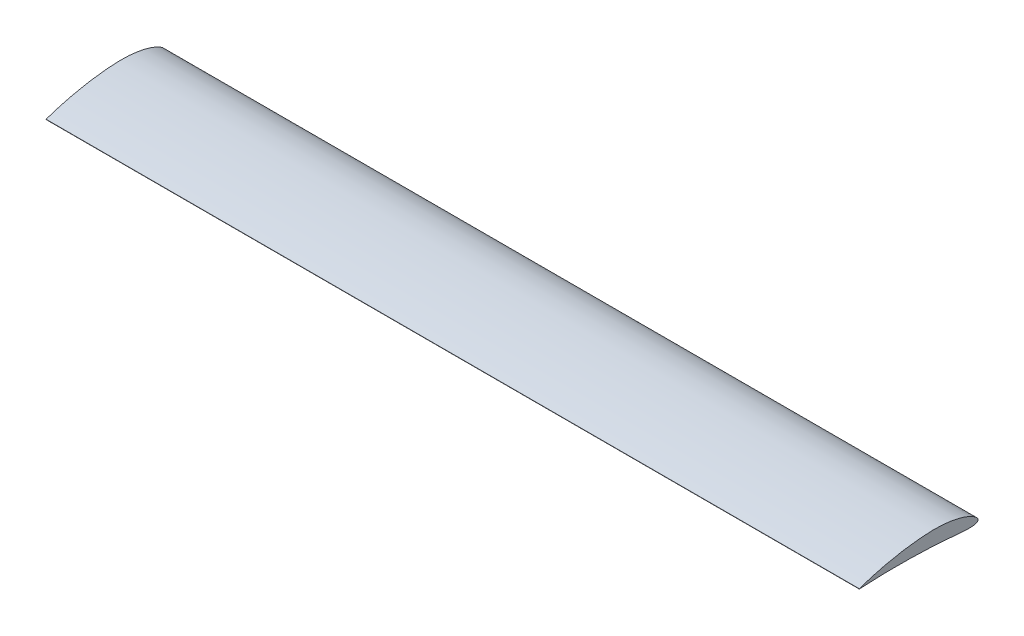
SolidWorks part; units mm, degrees
ref_plane "Front Plane" through (0, 0, 0) normal (0, 0, 1) x (1, 0, 0)
ref_plane "Top Plane" through (0, 0, 0) normal (0, 1, 0) x (1, 0, 0)
ref_plane "Right Plane" through (0, 0, 0) normal (1, 0, 0) x (0, 0, -1)
sketch3d "3DSketch3" plane through (0, 0, 0) normal (0, 0, 1) x (1, 0, 0)
  dimension "D1" = 2438.4
curve "Curve3"
  spline degree 3 poles (0, 0, 0) (0, -0.0634, 0.0198) (0, -0.1901, 0.0592) (0, -0.3772, 0.1273) (0, -0.5618, 0.2018) (0, -0.7437, 0.2832) (0, -0.923, 0.3715) (0, -1.0997, 0.4667) (0, -1.2737, 0.5687) (0, -1.4452, 0.6775) (0, -1.614, 0.7932) (0, -1.7802, 0.9157) (0, -1.9437, 1.045) (0, -2.1047, 1.181) (0, -2.2631, 1.3238) (0, -2.4188, 1.4735) (0, -2.5721, 1.6298) (0, -2.7222, 1.7933) (0, -2.8706, 1.9627) (0, -3.0158, 2.1392) (0, -3.1586, 2.3224) (0, -3.2988, 2.5123) (0, -3.4364, 2.7088) (0, -3.5714, 2.912) (0, -3.7039, 3.1219) (0, -3.8339, 3.3384) (0, -3.9613, 3.5614) (0, -4.0861, 3.7911) (0, -4.2084, 4.0274) (0, -4.3282, 4.2702) (0, -4.4454, 4.5196) (0, -4.5602, 4.7755) (0, -4.6724, 5.0379) (0, -4.7821, 5.3068) (0, -4.8894, 5.5822) (0, -4.9941, 5.8641) (0, -5.0964, 6.1524) (0, -5.1962, 6.4471) (0, -5.2935, 6.7483) (0, -5.3884, 7.0559) (0, -5.4809, 7.3698) (0, -5.5709, 7.6901) (0, -5.6585, 8.0167) (0, -5.7437, 8.3497) (0, -5.8264, 8.6889) (0, -5.9068, 9.0345) (0, -5.9848, 9.3863) (0, -6.0604, 9.7443) (0, -6.1337, 10.1086) (0, -6.2046, 10.4791) (0, -6.2732, 10.8558) (0, -6.3394, 11.2386) (0, -6.4033, 11.6276) (0, -6.4649, 12.0227) (0, -6.5242, 12.4239) (0, -6.5813, 12.8312) (0, -6.636, 13.2445) (0, -6.6885, 13.6639) (0, -6.7388, 14.0893) (0, -6.7868, 14.5207) (0, -6.8326, 14.958) (0, -6.8762, 15.4013) (0, -6.9176, 15.8506) (0, -6.9569, 16.3057) (0, -6.9939, 16.7667) (0, -7.0288, 17.2336) (0, -7.0616, 17.7063) (0, -7.0922, 18.1848) (0, -7.1208, 18.6691) (0, -7.1472, 19.1592) (0, -7.1716, 19.655) (0, -7.1939, 20.1565) (0, -7.2141, 20.6637) (0, -7.2323, 21.1766) (0, -7.2486, 21.6952) (0, -7.2628, 22.2193) (0, -7.275, 22.749) (0, -7.2852, 23.2844) (0, -7.2935, 23.8252) (0, -7.2999, 24.3716) (0, -7.3043, 24.9235) (0, -7.3069, 25.4808) (0, -7.3075, 26.0436) (0, -7.3063, 26.6118) (0, -7.3033, 27.1854) (0, -7.2984, 27.7644) (0, -7.2917, 28.3487) (0, -7.2832, 28.9383) (0, -7.273, 29.5332) (0, -7.2609, 30.1334) (0, -7.2472, 30.7389) (0, -7.2317, 31.3495) (0, -7.2145, 31.9653) (0, -7.1956, 32.5863) (0, -7.1751, 33.2124) (0, -7.1529, 33.8436) (0, -7.1291, 34.4799) (0, -7.1038, 35.1213) (0, -7.0768, 35.7677) (0, -7.0482, 36.4191) (0, -7.0182, 37.0755) (0, -6.9866, 37.7368) (0, -6.9534, 38.403) (0, -6.9189, 39.0741) (0, -6.8828, 39.7501) (0, -6.8453, 40.431) (0, -6.8064, 41.1166) (0, -6.7662, 41.807) (0, -6.7245, 42.5022) (0, -6.6815, 43.2022) (0, -6.6371, 43.9068) (0, -6.5915, 44.6161) (0, -6.5445, 45.3301) (0, -6.4963, 46.0486) (0, -6.4469, 46.7718) (0, -6.3962, 47.4996) (0, -6.3444, 48.2318) (0, -6.2914, 48.9686) (0, -6.2372, 49.7099) (0, -6.1819, 50.4557) (0, -6.1255, 51.2059) (0, -6.068, 51.9604) (0, -6.0095, 52.7194) (0, -5.9499, 53.4827) (0, -5.8894, 54.2503) (0, -5.8278, 55.0222) (0, -5.7653, 55.7984) (0, -5.7018, 56.5788) (0, -5.6375, 57.3635) (0, -5.5722, 58.1523) (0, -5.5061, 58.9453) (0, -5.4392, 59.7424) (0, -5.3714, 60.5436) (0, -5.3029, 61.3488) (0, -5.2336, 62.1581) (0, -5.1635, 62.9715) (0, -5.0927, 63.7888) (0, -5.0213, 64.6101) (0, -4.9492, 65.4353) (0, -4.8764, 66.2644) (0, -4.8031, 67.0974) (0, -4.7291, 67.9343) (0, -4.6546, 68.7749) (0, -4.5796, 69.6194) (0, -4.504, 70.4677) (0, -4.428, 71.3196) (0, -4.3515, 72.1753) (0, -4.2746, 73.0347) (0, -4.1972, 73.8977) (0, -4.1195, 74.7644) (0, -4.0414, 75.6346) (0, -3.9631, 76.5085) (0, -3.8844, 77.3858) (0, -3.8054, 78.2667) (0, -3.7262, 79.1511) (0, -3.6467, 80.0389) (0, -3.5671, 80.9302) (0, -3.4873, 81.8249) (0, -3.4073, 82.7229) (0, -3.3272, 83.6243) (0, -3.247, 84.529) (0, -3.1668, 85.437) (0, -3.0865, 86.3483) (0, -3.0062, 87.2628) (0, -2.926, 88.1805) (0, -2.8457, 89.1014) (0, -2.7656, 90.0255) (0, -2.6855, 90.9526) (0, -2.6055, 91.8829) (0, -2.5257, 92.8162) (0, -2.4461, 93.7526) (0, -2.3666, 94.692) (0, -2.2874, 95.6343) (0, -2.2084, 96.5796) (0, -2.1297, 97.5279) (0, -2.0514, 98.479) (0, -1.9733, 99.433) (0, -1.8956, 100.3898) (0, -1.8182, 101.3494) (0, -1.7413, 102.3118) (0, -1.6648, 103.277) (0, -1.5888, 104.2449) (0, -1.5132, 105.2155) (0, -1.4382, 106.1887) (0, -1.3636, 107.1646) (0, -1.2897, 108.1431) (0, -1.2163, 109.1241) (0, -1.1435, 110.1077) (0, -1.0714, 111.0938) (0, -0.9999, 112.0824) (0, -0.9291, 113.0735) (0, -0.8591, 114.067) (0, -0.7897, 115.0629) (0, -0.7211, 116.0611) (0, -0.6533, 117.0617) (0, -0.5863, 118.0646) (0, -0.5201, 119.0698) (0, -0.4548, 120.0772) (0, -0.3904, 121.0869) (0, -0.3268, 122.0987) (0, -0.2642, 123.1127) (0, -0.2025, 124.1288) (0, -0.1418, 125.147) (0, -0.0821, 126.1672) (0, -0.0234, 127.1895) (0, 0.0343, 128.2138) (0, 0.0908, 129.2401) (0, 0.1464, 130.2683) (0, 0.2008, 131.2984) (0, 0.2541, 132.3304) (0, 0.3062, 133.3643) (0, 0.3572, 134.3999) (0, 0.4069, 135.4374) (0, 0.4555, 136.4765) (0, 0.5028, 137.5174) (0, 0.5489, 138.56) (0, 0.5937, 139.6043) (0, 0.6372, 140.6501) (0, 0.6797, 141.7018) (0, 0.7205, 142.7639) (0, 0.7611, 143.8363) (0, 0.8019, 144.9147) (0, 0.8426, 145.9944) (0, 0.8833, 147.0755) (0, 0.9239, 148.1578) (0, 0.9644, 149.2414) (0, 1.0047, 150.3263) (0, 1.045, 151.4122) (0, 1.0852, 152.4994) (0, 1.1252, 153.5876) (0, 1.165, 154.6768) (0, 1.2047, 155.7671) (0, 1.2442, 156.8584) (0, 1.2835, 157.9505) (0, 1.3226, 159.0436) (0, 1.3615, 160.1375) (0, 1.4001, 161.2323) (0, 1.4385, 162.3278) (0, 1.4767, 163.424) (0, 1.5146, 164.5209) (0, 1.5522, 165.6185) (0, 1.5896, 166.7167) (0, 1.6266, 167.8154) (0, 1.6634, 168.9147) (0, 1.6998, 170.0145) (0, 1.7359, 171.1147) (0, 1.7717, 172.2153) (0, 1.8071, 173.3162) (0, 1.8422, 174.4175) (0, 1.8769, 175.5191) (0, 1.9113, 176.6209) (0, 1.9452, 177.7229) (0, 1.9788, 178.825) (0, 2.0119, 179.9273) (0, 2.0447, 181.0297) (0, 2.077, 182.132) (0, 2.1089, 183.2344) (0, 2.1404, 184.3367) (0, 2.1714, 185.4389) (0, 2.202, 186.541) (0, 2.2321, 187.6429) (0, 2.2617, 188.7446) (0, 2.2909, 189.846) (0, 2.3196, 190.9471) (0, 2.3478, 192.0478) (0, 2.3755, 193.1482) (0, 2.4027, 194.2482) (0, 2.4294, 195.3476) (0, 2.4556, 196.4466) (0, 2.4812, 197.545) (0, 2.5064, 198.6428) (0, 2.531, 199.7399) (0, 2.5551, 200.8364) (0, 2.5786, 201.9321) (0, 2.6016, 203.0271) (0, 2.624, 204.1213) (0, 2.6459, 205.2146) (0, 2.6672, 206.307) (0, 2.688, 207.3985) (0, 2.7082, 208.489) (0, 2.7278, 209.5785) (0, 2.7468, 210.6669) (0, 2.7653, 211.7542) (0, 2.7832, 212.8403) (0, 2.8005, 213.9253) (0, 2.8172, 215.009) (0, 2.8333, 216.0915) (0, 2.8488, 217.1726) (0, 2.8638, 218.2524) (0, 2.8781, 219.3307) (0, 2.8918, 220.4076) (0, 2.905, 221.483) (0, 2.9175, 222.5569) (0, 2.9294, 223.6292) (0, 2.9408, 224.6999) (0, 2.9515, 225.769) (0, 2.9616, 226.8363) (0, 2.9711, 227.9019) (0, 2.98, 228.9657) (0, 2.9883, 230.0277) (0, 2.996, 231.0878) (0, 3.0031, 232.146) (0, 3.0096, 233.2022) (0, 3.0155, 234.2564) (0, 3.0208, 235.3086) (0, 3.0255, 236.3587) (0, 3.0295, 237.4067) (0, 3.033, 238.4525) (0, 3.0359, 239.4962) (0, 3.0382, 240.5375) (0, 3.0399, 241.5766) (0, 3.0409, 242.6133) (0, 3.0414, 243.6477) (0, 3.0414, 244.6796) (0, 3.0407, 245.7091) (0, 3.0394, 246.7361) (0, 3.0376, 247.7605) (0, 3.0352, 248.7824) (0, 3.0322, 249.8016) (0, 3.0287, 250.8182) (0, 3.0245, 251.832) (0, 3.0199, 252.8431) (0, 3.0146, 253.8514) (0, 3.0088, 254.8569) (0, 3.0025, 255.8595) (0, 2.9956, 256.8592) (0, 2.9881, 257.856) (0, 2.9802, 258.8497) (0, 2.9716, 259.8404) (0, 2.9626, 260.828) (0, 2.953, 261.8126) (0, 2.943, 262.7939) (0, 2.9324, 263.7721) (0, 2.9213, 264.747) (0, 2.9097, 265.7186) (0, 2.8976, 266.6869) (0, 2.885, 267.6519) (0, 2.8719, 268.6135) (0, 2.8583, 269.5716) (0, 2.8443, 270.5262) (0, 2.8298, 271.4773) (0, 2.8148, 272.4249) (0, 2.7994, 273.3689) (0, 2.7835, 274.3092) (0, 2.7672, 275.2459) (0, 2.7505, 276.1788) (0, 2.7333, 277.108) (0, 2.7157, 278.0334) (0, 2.6977, 278.955) (0, 2.6793, 279.8726) (0, 2.6604, 280.7864) (0, 2.6412, 281.6963) (0, 2.6216, 282.6021) (0, 2.6016, 283.504) (0, 2.5813, 284.4017) (0, 2.5606, 285.2954) (0, 2.5395, 286.1849) (0, 2.518, 287.0703) (0, 2.4963, 287.9514) (0, 2.4742, 288.8283) (0, 2.4517, 289.701) (0, 2.429, 290.5693) (0, 2.4059, 291.4332) (0, 2.3825, 292.2927) (0, 2.3588, 293.1478) (0, 2.3349, 293.9985) (0, 2.3106, 294.8446) (0, 2.2861, 295.6862) (0, 2.2613, 296.5232) (0, 2.2363, 297.3556) (0, 2.211, 298.1834) (0, 2.1855, 299.0064) (0, 2.1597, 299.8248) (0, 2.1337, 300.6384) (0, 2.1075, 301.4472) (0, 2.0811, 302.2512) (0, 2.0545, 303.0503) (0, 2.0277, 303.8445) (0, 2.0008, 304.6338) (0, 1.9736, 305.4182) (0, 1.9463, 306.1975) (0, 1.9188, 306.9718) (0, 1.8912, 307.7411) (0, 1.8634, 308.5052) (0, 1.8355, 309.2643) (0, 1.8074, 310.0181) (0, 1.7793, 310.7668) (0, 1.751, 311.5103) (0, 1.7227, 312.2485) (0, 1.6942, 312.9814) (0, 1.6657, 313.709) (0, 1.6371, 314.4312) (0, 1.6084, 315.148) (0, 1.5796, 315.8594) (0, 1.5508, 316.5654) (0, 1.522, 317.2659) (0, 1.4931, 317.9609) (0, 1.4642, 318.6503) (0, 1.4353, 319.3342) (0, 1.4064, 320.0125) (0, 1.3774, 320.6851) (0, 1.3485, 321.3521) (0, 1.3195, 322.0133) (0, 1.2906, 322.6689) (0, 1.2618, 323.3187) (0, 1.2329, 323.9628) (0, 1.2041, 324.601) (0, 1.1754, 325.2334) (0, 1.1467, 325.86) (0, 1.118, 326.4806) (0, 1.0895, 327.0953) (0, 1.061, 327.7041) (0, 1.0326, 328.3069) (0, 1.0043, 328.9038) (0, 0.9761, 329.4946) (0, 0.9481, 330.0793) (0, 0.9201, 330.658) (0, 0.8923, 331.2305) (0, 0.8646, 331.797) (0, 0.837, 332.3572) (0, 0.8096, 332.9113) (0, 0.7823, 333.4592) (0, 0.7552, 334.0009) (0, 0.7282, 334.5363) (0, 0.7014, 335.0654) (0, 0.6748, 335.5883) (0, 0.6484, 336.1048) (0, 0.6222, 336.6149) (0, 0.5962, 337.1187) (0, 0.5704, 337.6161) (0, 0.5448, 338.1071) (0, 0.5194, 338.5916) (0, 0.4942, 339.0697) (0, 0.4693, 339.5413) (0, 0.4445, 340.0064) (0, 0.4201, 340.465) (0, 0.3959, 340.917) (0, 0.3719, 341.3625) (0, 0.3482, 341.8013) (0, 0.3247, 342.2336) (0, 0.3016, 342.6593) (0, 0.2787, 343.0782) (0, 0.2561, 343.4906) (0, 0.2337, 343.8962) (0, 0.2117, 344.2952) (0, 0.1899, 344.6874) (0, 0.1685, 345.0729) (0, 0.1473, 345.4516) (0, 0.1265, 345.8236) (0, 0.106, 346.1887) (0, 0.0858, 346.5471) (0, 0.0659, 346.8986) (0, 0.0464, 347.2433) (0, 0.027, 347.5812) (0, 0.0083, 347.9122) (0, -0.0102, 348.2362) (0, -0.0286, 348.5534) (0, -0.0462, 348.8637) (0, -0.0638, 349.167) (0, -0.0809, 349.4634) (0, -0.0977, 349.7529) (0, -0.1141, 350.0353) (0, -0.1301, 350.3108) (0, -0.1458, 350.5793) (0, -0.161, 350.8408) (0, -0.1759, 351.0952) (0, -0.1905, 351.3427) (0, -0.2046, 351.583) (0, -0.2183, 351.8164) (0, -0.2317, 352.0426) (0, -0.2447, 352.2618) (0, -0.2572, 352.4739) (0, -0.2694, 352.6789) (0, -0.2811, 352.8768) (0, -0.2925, 353.0675) (0, -0.3034, 353.2512) (0, -0.314, 353.4277) (0, -0.3241, 353.5971) (0, -0.3338, 353.7593) (0, -0.3431, 353.9144) (0, -0.352, 354.0623) (0, -0.3604, 354.203) (0, -0.3684, 354.3365) (0, -0.3761, 354.4629) (0, -0.3832, 354.5821) (0, -0.39, 354.6941) (0, -0.3963, 354.7989) (0, -0.4022, 354.8964) (0, -0.4077, 354.9868) (0, -0.4127, 355.07) (0, -0.4173, 355.1459) (0, -0.4214, 355.2146) (0, -0.4252, 355.2761) (0, -0.4285, 355.3304) (0, -0.4313, 355.3774) (0, -0.4337, 355.4172) (0, -0.4357, 355.4498) (0, -0.4372, 355.4751) (0, -0.4383, 355.4932) (0, -0.439, 355.5041) (0, -0.4393, 355.5089) (0, -0.4394, 355.5101) knots 0 0 0 0 0.000556 0.001111 0.001666 0.002222 0.00278 0.00334 0.003902 0.004469 0.00504 0.005616 0.006197 0.006785 0.00738 0.007983 0.008593 0.009214 0.009841 0.010479 0.011127 0.011786 0.012455 0.013136 0.013829 0.014533 0.01525 0.01598 0.016722 0.017478 0.018247 0.019029 0.019826 0.020637 0.021461 0.022301 0.023154 0.024023 0.024906 0.025805 0.026718 0.027647 0.028591 0.02955 0.030525 0.031515 0.032521 0.033542 0.034579 0.035632 0.036701 0.037785 0.038885 0.040001 0.041133 0.042281 0.043445 0.044625 0.04582 0.047032 0.048259 0.049503 0.050762 0.052037 0.053328 0.054635 0.055957 0.057296 0.05865 0.06002 0.061406 0.062807 0.064224 0.065656 0.067104 0.068568 0.070047 0.071541 0.073051 0.074576 0.076117 0.077673 0.079244 0.08083 0.082431 0.084047 0.085678 0.087324 0.088985 0.09066 0.092351 0.094056 0.095775 0.097509 0.099258 0.101021 0.102798 0.10459 0.106396 0.108216 0.11005 0.111898 0.11376 0.115636 0.117525 0.119428 0.121345 0.123276 0.12522 0.127177 0.129148 0.131132 0.133129 0.135139 0.137163 0.139199 0.141248 0.14331 0.145385 0.147472 0.149572 0.151684 0.153809 0.155946 0.158095 0.160257 0.16243 0.164616 0.166813 0.169023 0.171244 0.173476 0.175721 0.177977 0.180244 0.182523 0.184813 0.187114 0.189426 0.191749 0.194083 0.196428 0.198784 0.20115 0.203527 0.205915 0.208313 0.210721 0.21314 0.215569 0.218008 0.220456 0.222915 0.225384 0.227862 0.23035 0.232848 0.235355 0.237872 0.240398 0.242933 0.245478 0.248031 0.250593 0.253165 0.255745 0.258334 0.260932 0.263538 0.266153 0.268776 0.271407 0.274047 0.276695 0.27935 0.282014 0.284686 0.287366 0.290053 0.292748 0.29545 0.29816 0.300878 0.303602 0.306334 0.309073 0.311819 0.314572 0.317332 0.320099 0.322872 0.325652 0.328439 0.331232 0.334031 0.336836 0.339648 0.342466 0.34529 0.34812 0.350956 0.353797 0.356644 0.359497 0.362355 0.365219 0.368088 0.370962 0.373841 0.376726 0.379615 0.382509 0.385408 0.388312 0.391221 0.394134 0.397051 0.399973 0.402899 0.405865 0.408873 0.411885 0.414901 0.417921 0.420944 0.423971 0.427001 0.430035 0.433071 0.436111 0.439153 0.442199 0.445246 0.448297 0.45135 0.454405 0.457463 0.460523 0.463585 0.466648 0.469714 0.472781 0.475849 0.47892 0.481991 0.485064 0.488137 0.491212 0.494288 0.497364 0.500441 0.503518 0.506596 0.509674 0.512753 0.515831 0.518909 0.521987 0.525065 0.528142 0.531219 0.534296 0.537371 0.540445 0.543519 0.546591 0.549663 0.552733 0.555801 0.558868 0.561933 0.564996 0.568057 0.571117 0.574174 0.577228 0.580281 0.583331 0.586378 0.589422 0.592464 0.595502 0.598538 0.60157 0.604599 0.607624 0.610646 0.613664 0.616678 0.619688 0.622694 0.625696 0.628694 0.631687 0.634676 0.63766 0.64064 0.643614 0.646584 0.649548 0.652507 0.655461 0.658409 0.661352 0.664289 0.66722 0.670145 0.673065 0.675978 0.678884 0.681785 0.684679 0.687566 0.690446 0.69332 0.696186 0.699046 0.701898 0.704743 0.707581 0.710411 0.713233 0.716048 0.718854 0.721653 0.724443 0.727226 0.729999 0.732765 0.735522 0.73827 0.741009 0.74374 0.746461 0.749174 0.751877 0.75457 0.757255 0.759929 0.762594 0.765249 0.767895 0.77053 0.773155 0.77577 0.778374 0.780968 0.783552 0.786125 0.788687 0.791238 0.793778 0.796307 0.798825 0.801332 0.803827 0.806311 0.808783 0.811243 0.813691 0.816128 0.818552 0.820965 0.823365 0.825753 0.828128 0.830491 0.832841 0.835178 0.837503 0.839814 0.842113 0.844398 0.84667 0.848929 0.851174 0.853406 0.855624 0.857829 0.86002 0.862196 0.864359 0.866508 0.868642 0.870762 0.872868 0.874959 0.877036 0.879098 0.881145 0.883178 0.885195 0.887198 0.889185 0.891157 0.893114 0.895056 0.896982 0.898892 0.900787 0.902667 0.90453 0.906378 0.908209 0.910025 0.911824 0.913608 0.915375 0.917125 0.91886 0.920577 0.922279 0.923963 0.925631 0.927282 0.928916 0.930533 0.932133 0.933716 0.935282 0.93683 0.938362 0.939875 0.941372 0.942851 0.944312 0.945756 0.947181 0.94859 0.94998 0.951352 0.952707 0.954043 0.955361 0.956661 0.957943 0.959206 0.960452 0.961678 0.962887 0.964077 0.965248 0.966401 0.967535 0.96865 0.969746 0.970824 0.971883 0.972923 0.973944 0.974945 0.975928 0.976892 0.977837 0.978762 0.979668 0.980555 0.981422 0.98227 0.983099 0.983908 0.984698 0.985468 0.986219 0.98695 0.987662 0.988353 0.989026 0.989678 0.990311 0.990923 0.991517 0.99209 0.992643 0.993177 0.99369 0.994184 0.994657 0.995111 0.995544 0.995958 0.996352 0.996725 0.997078 0.997412 0.997725 0.998018 0.998291 0.998543 0.998776 0.998988 0.99918 0.999352 0.999504 0.999636 0.999747 0.999838 0.999909 0.99996 0.99999 1 1 1 1
curve "Curve4"
  spline degree 3 poles (0, 0, 0) (0, 0.0638, -0.0184) (0, 0.1913, -0.0552) (0, 0.385, -0.1013) (0, 0.5801, -0.1407) (0, 0.7768, -0.1727) (0, 0.9752, -0.1976) (0, 1.1751, -0.2151) (0, 1.3767, -0.2255) (0, 1.5798, -0.2285) (0, 1.7845, -0.2243) (0, 1.9908, -0.2128) (0, 2.1987, -0.1941) (0, 2.4081, -0.168) (0, 2.6191, -0.1347) (0, 2.8317, -0.0941) (0, 3.0458, -0.0461) (0, 3.2614, 0.0091) (0, 3.4786, 0.0716) (0, 3.6973, 0.1414) (0, 3.9175, 0.2185) (0, 4.1392, 0.303) (0, 4.3625, 0.3947) (0, 4.5872, 0.4938) (0, 4.8133, 0.6002) (0, 5.041, 0.7139) (0, 5.2701, 0.8349) (0, 5.5006, 0.9632) (0, 5.7325, 1.0989) (0, 5.9659, 1.2419) (0, 6.2006, 1.3922) (0, 6.4368, 1.5498) (0, 6.6743, 1.7147) (0, 6.9131, 1.887) (0, 7.1533, 2.0666) (0, 7.3948, 2.2535) (0, 7.6375, 2.4477) (0, 7.8816, 2.6493) (0, 8.1269, 2.8582) (0, 8.3735, 3.0743) (0, 8.6213, 3.2978) (0, 8.8703, 3.5286) (0, 9.1204, 3.7667) (0, 9.3718, 4.0122) (0, 9.6242, 4.2649) (0, 9.8778, 4.5249) (0, 10.1325, 4.7921) (0, 10.3882, 5.0667) (0, 10.645, 5.3486) (0, 10.9028, 5.6377) (0, 11.1616, 5.9341) (0, 11.4214, 6.2378) (0, 11.6822, 6.5487) (0, 11.9438, 6.8668) (0, 12.2064, 7.1922) (0, 12.4698, 7.5249) (0, 12.734, 7.8648) (0, 12.9991, 8.2118) (0, 13.265, 8.5661) (0, 13.5316, 8.9276) (0, 13.7989, 9.2963) (0, 14.067, 9.6722) (0, 14.3357, 10.0553) (0, 14.6051, 10.4455) (0, 14.875, 10.8428) (0, 15.1456, 11.2473) (0, 15.4167, 11.659) (0, 15.6883, 12.0777) (0, 15.9604, 12.5036) (0, 16.233, 12.9366) (0, 16.5059, 13.3766) (0, 16.7793, 13.8237) (0, 17.0531, 14.2779) (0, 17.3271, 14.7391) (0, 17.6015, 15.2073) (0, 17.8761, 15.6825) (0, 18.1509, 16.1648) (0, 18.4259, 16.654) (0, 18.7011, 17.1502) (0, 18.9764, 17.6533) (0, 19.2518, 18.1634) (0, 19.5272, 18.6804) (0, 19.8026, 19.2042) (0, 20.078, 19.735) (0, 20.3534, 20.2726) (0, 20.6287, 20.8171) (0, 20.9038, 21.3684) (0, 21.1787, 21.9265) (0, 21.4535, 22.4914) (0, 21.728, 23.0631) (0, 22.0023, 23.6415) (0, 22.2762, 24.2266) (0, 22.5498, 24.8185) (0, 22.8229, 25.417) (0, 23.0957, 26.0222) (0, 23.368, 26.634) (0, 23.6398, 27.2524) (0, 23.911, 27.8775) (0, 24.1817, 28.5091) (0, 24.4517, 29.1472) (0, 24.7211, 29.7919) (0, 24.9898, 30.443) (0, 25.2577, 31.1007) (0, 25.5249, 31.7648) (0, 25.7913, 32.4353) (0, 26.0568, 33.1122) (0, 26.3214, 33.7954) (0, 26.5851, 34.485) (0, 26.8478, 35.1809) (0, 27.1096, 35.8831) (0, 27.3702, 36.5916) (0, 27.6298, 37.3062) (0, 27.8883, 38.0271) (0, 28.1456, 38.7542) (0, 28.4017, 39.4873) (0, 28.6566, 40.2266) (0, 28.9102, 40.972) (0, 29.1625, 41.7234) (0, 29.4134, 42.4808) (0, 29.6629, 43.2442) (0, 29.911, 44.0136) (0, 30.1577, 44.7888) (0, 30.4028, 45.57) (0, 30.6464, 46.357) (0, 30.8884, 47.1498) (0, 31.1287, 47.9484) (0, 31.3674, 48.7528) (0, 31.6044, 49.5628) (0, 31.8397, 50.3786) (0, 32.0732, 51.2) (0, 32.3049, 52.0269) (0, 32.5347, 52.8595) (0, 32.7627, 53.6976) (0, 32.9887, 54.5412) (0, 33.2128, 55.3902) (0, 33.4349, 56.2446) (0, 33.6549, 57.1045) (0, 33.8729, 57.9697) (0, 34.0888, 58.8401) (0, 34.3026, 59.7159) (0, 34.5141, 60.5968) (0, 34.7235, 61.483) (0, 34.9306, 62.3743) (0, 35.1355, 63.2707) (0, 35.338, 64.1721) (0, 35.5382, 65.0786) (0, 35.736, 65.99) (0, 35.9314, 66.9064) (0, 36.1244, 67.8277) (0, 36.3149, 68.7538) (0, 36.5029, 69.6847) (0, 36.6883, 70.6204) (0, 36.8712, 71.5608) (0, 37.0514, 72.5059) (0, 37.229, 73.4556) (0, 37.404, 74.4099) (0, 37.5762, 75.3688) (0, 37.7458, 76.3321) (0, 37.9125, 77.2999) (0, 38.0765, 78.2721) (0, 38.2377, 79.2486) (0, 38.396, 80.2295) (0, 38.5514, 81.2146) (0, 38.704, 82.204) (0, 38.8536, 83.1975) (0, 39.0002, 84.1951) (0, 39.1439, 85.1968) (0, 39.2846, 86.2026) (0, 39.4222, 87.2123) (0, 39.5567, 88.2259) (0, 39.6882, 89.2434) (0, 39.8166, 90.2648) (0, 39.9418, 91.2899) (0, 40.0639, 92.3188) (0, 40.1828, 93.3514) (0, 40.2985, 94.3876) (0, 40.4109, 95.4274) (0, 40.5202, 96.4707) (0, 40.6261, 97.5175) (0, 40.7287, 98.5677) (0, 40.8281, 99.6213) (0, 40.9241, 100.6783) (0, 41.0167, 101.7385) (0, 41.106, 102.8019) (0, 41.1919, 103.8686) (0, 41.2744, 104.9383) (0, 41.3534, 106.0112) (0, 41.429, 107.087) (0, 41.5011, 108.1658) (0, 41.5698, 109.2476) (0, 41.635, 110.3322) (0, 41.6966, 111.4196) (0, 41.7548, 112.5098) (0, 41.8094, 113.6026) (0, 41.8604, 114.6982) (0, 41.9079, 115.7963) (0, 41.9518, 116.897) (0, 41.9921, 118.0002) (0, 42.0288, 119.1058) (0, 42.0619, 120.2138) (0, 42.0913, 121.3241) (0, 42.1173, 122.4368) (0, 42.139, 123.5516) (0, 42.1592, 124.6686) (0, 42.1676, 125.7878) (0, 42.1543, 126.9092) (0, 42.1994, 128.032) (0, 42.1931, 129.1574) (0, 42.196, 130.2845) (0, 42.1917, 131.4134) (0, 42.1846, 132.5441) (0, 42.1736, 133.6766) (0, 42.1589, 134.8108) (0, 42.1405, 135.9466) (0, 42.1183, 137.0839) (0, 42.0925, 138.2228) (0, 42.0629, 139.3632) (0, 42.0295, 140.505) (0, 41.9927, 141.6439) (0, 41.9519, 142.7753) (0, 41.9085, 143.8991) (0, 41.8633, 145.0197) (0, 41.8158, 146.1414) (0, 41.7661, 147.2644) (0, 41.7142, 148.3885) (0, 41.66, 149.5137) (0, 41.6037, 150.64) (0, 41.5452, 151.7672) (0, 41.4845, 152.8954) (0, 41.4216, 154.0245) (0, 41.3565, 155.1544) (0, 41.2893, 156.2851) (0, 41.2199, 157.4166) (0, 41.1484, 158.5488) (0, 41.0747, 159.6817) (0, 40.9989, 160.8151) (0, 40.921, 161.9492) (0, 40.841, 163.0837) (0, 40.7588, 164.2187) (0, 40.6746, 165.3541) (0, 40.5883, 166.4899) (0, 40.4999, 167.626) (0, 40.4094, 168.7624) (0, 40.3169, 169.8991) (0, 40.2223, 171.0359) (0, 40.1257, 172.1728) (0, 40.0271, 173.3098) (0, 39.9265, 174.4469) (0, 39.8238, 175.5839) (0, 39.7192, 176.7209) (0, 39.6126, 177.8578) (0, 39.504, 178.9945) (0, 39.3935, 180.1311) (0, 39.281, 181.2674) (0, 39.1666, 182.4033) (0, 39.0503, 183.539) (0, 38.9321, 184.6743) (0, 38.8119, 185.8091) (0, 38.6899, 186.9434) (0, 38.5661, 188.0773) (0, 38.4404, 189.2105) (0, 38.3128, 190.3431) (0, 38.1834, 191.4751) (0, 38.0523, 192.6063) (0, 37.9193, 193.7368) (0, 37.7845, 194.8665) (0, 37.648, 195.9953) (0, 37.5097, 197.1232) (0, 37.3697, 198.2502) (0, 37.228, 199.3761) (0, 37.0845, 200.5011) (0, 36.9394, 201.6249) (0, 36.7926, 202.7477) (0, 36.6441, 203.8692) (0, 36.494, 204.9895) (0, 36.3423, 206.1086) (0, 36.1889, 207.2263) (0, 36.034, 208.3427) (0, 35.8775, 209.4577) (0, 35.7194, 210.5712) (0, 35.5598, 211.6833) (0, 35.3986, 212.7938) (0, 35.236, 213.9027) (0, 35.0718, 215.01) (0, 34.9062, 216.1157) (0, 34.7391, 217.2196) (0, 34.5706, 218.3217) (0, 34.4007, 219.4221) (0, 34.2293, 220.5206) (0, 34.0566, 221.6172) (0, 33.8825, 222.7119) (0, 33.707, 223.8046) (0, 33.5303, 224.8953) (0, 33.3522, 225.9839) (0, 33.1728, 227.0704) (0, 32.9921, 228.1547) (0, 32.8102, 229.2369) (0, 32.6271, 230.3168) (0, 32.4427, 231.3944) (0, 32.2571, 232.4697) (0, 32.0704, 233.5427) (0, 31.8825, 234.6132) (0, 31.6935, 235.6813) (0, 31.5033, 236.7469) (0, 31.3121, 237.81) (0, 31.1197, 238.8704) (0, 30.9263, 239.9283) (0, 30.7319, 240.9835) (0, 30.5365, 242.036) (0, 30.34, 243.0858) (0, 30.1426, 244.1328) (0, 29.9443, 245.1769) (0, 29.7449, 246.2182) (0, 29.5447, 247.2566) (0, 29.3436, 248.2921) (0, 29.1416, 249.3245) (0, 28.9388, 250.354) (0, 28.7351, 251.3804) (0, 28.5307, 252.4036) (0, 28.3254, 253.4238) (0, 28.1194, 254.4407) (0, 27.9126, 255.4544) (0, 27.7051, 256.4649) (0, 27.4969, 257.472) (0, 27.2881, 258.4759) (0, 27.0785, 259.4763) (0, 26.8684, 260.4733) (0, 26.6576, 261.4669) (0, 26.4463, 262.457) (0, 26.2343, 263.4435) (0, 26.0219, 264.4265) (0, 25.8089, 265.4059) (0, 25.5954, 266.3816) (0, 25.3814, 267.3537) (0, 25.167, 268.322) (0, 24.9521, 269.2866) (0, 24.7368, 270.2474) (0, 24.5212, 271.2043) (0, 24.3051, 272.1574) (0, 24.0888, 273.1066) (0, 23.8721, 274.0519) (0, 23.6551, 274.9932) (0, 23.4378, 275.9305) (0, 23.2203, 276.8637) (0, 23.0026, 277.7929) (0, 22.7847, 278.718) (0, 22.5665, 279.6389) (0, 22.3483, 280.5556) (0, 22.1299, 281.4682) (0, 21.9113, 282.3764) (0, 21.6927, 283.2804) (0, 21.4741, 284.1801) (0, 21.2553, 285.0754) (0, 21.0366, 285.9664) (0, 20.8179, 286.8529) (0, 20.5992, 287.735) (0, 20.3805, 288.6126) (0, 20.162, 289.4856) (0, 19.9435, 290.3542) (0, 19.7252, 291.2181) (0, 19.507, 292.0775) (0, 19.2889, 292.9322) (0, 19.0711, 293.7822) (0, 18.8535, 294.6275) (0, 18.6361, 295.4681) (0, 18.419, 296.3039) (0, 18.2022, 297.1349) (0, 17.9857, 297.9611) (0, 17.7695, 298.7825) (0, 17.5537, 299.5989) (0, 17.3383, 300.4104) (0, 17.1233, 301.217) (0, 16.9087, 302.0186) (0, 16.6945, 302.8152) (0, 16.4809, 303.6068) (0, 16.2677, 304.3933) (0, 16.0551, 305.1747) (0, 15.843, 305.951) (0, 15.6315, 306.7221) (0, 15.4205, 307.4881) (0, 15.2102, 308.2488) (0, 15.0006, 309.0043) (0, 14.7916, 309.7546) (0, 14.5833, 310.4996) (0, 14.3757, 311.2392) (0, 14.1688, 311.9736) (0, 13.9627, 312.7025) (0, 13.7573, 313.4261) (0, 13.5528, 314.1443) (0, 13.3491, 314.857) (0, 13.1463, 315.5642) (0, 12.9443, 316.266) (0, 12.7432, 316.9622) (0, 12.543, 317.6529) (0, 12.3438, 318.338) (0, 12.1455, 319.0176) (0, 11.9482, 319.6915) (0, 11.752, 320.3598) (0, 11.5567, 321.0224) (0, 11.3625, 321.6793) (0, 11.1694, 322.3306) (0, 10.9774, 322.9761) (0, 10.7865, 323.6158) (0, 10.5967, 324.2498) (0, 10.4081, 324.8779) (0, 10.2207, 325.5003) (0, 10.0345, 326.1168) (0, 9.8495, 326.7274) (0, 9.6658, 327.3322) (0, 9.4833, 327.931) (0, 9.3021, 328.5239) (0, 9.1223, 329.1109) (0, 8.9437, 329.6919) (0, 8.7665, 330.2669) (0, 8.5907, 330.8359) (0, 8.4163, 331.3989) (0, 8.2433, 331.9558) (0, 8.0718, 332.5067) (0, 7.9016, 333.0515) (0, 7.733, 333.5902) (0, 7.5659, 334.1227) (0, 7.4002, 334.6492) (0, 7.2362, 335.1694) (0, 7.0736, 335.6835) (0, 6.9126, 336.1914) (0, 6.7533, 336.6931) (0, 6.5955, 337.1885) (0, 6.4394, 337.6777) (0, 6.2849, 338.1607) (0, 6.1321, 338.6374) (0, 5.9809, 339.1078) (0, 5.8315, 339.5718) (0, 5.6838, 340.0296) (0, 5.5378, 340.481) (0, 5.3936, 340.926) (0, 5.2511, 341.3647) (0, 5.1105, 341.797) (0, 4.9716, 342.2229) (0, 4.8346, 342.6424) (0, 4.6994, 343.0554) (0, 4.5661, 343.462) (0, 4.4346, 343.8622) (0, 4.305, 344.2559) (0, 4.1774, 344.6431) (0, 4.0516, 345.0238) (0, 3.9278, 345.398) (0, 3.8059, 345.7657) (0, 3.686, 346.1268) (0, 3.5681, 346.4814) (0, 3.4521, 346.8294) (0, 3.3385, 347.171) (0, 3.2253, 347.5055) (0, 3.12, 347.8366) (0, 2.9939, 348.1528) (0, 2.8977, 348.4717) (0, 2.7952, 348.7798) (0, 2.6918, 349.0804) (0, 2.5994, 349.3774) (0, 2.5004, 349.6649) (0, 2.4056, 349.947) (0, 2.3123, 350.2222) (0, 2.2214, 350.4907) (0, 2.1326, 350.7526) (0, 2.0459, 351.0078) (0, 1.9614, 351.2562) (0, 1.8792, 351.498) (0, 1.7991, 351.733) (0, 1.7212, 351.9613) (0, 1.6456, 352.1828) (0, 1.5722, 352.3977) (0, 1.501, 352.6057) (0, 1.432, 352.807) (0, 1.3654, 353.0016) (0, 1.3009, 353.1894) (0, 1.2388, 353.3704) (0, 1.1789, 353.5446) (0, 1.1214, 353.712) (0, 1.0661, 353.8727) (0, 1.0131, 354.0265) (0, 0.9624, 354.1736) (0, 0.9141, 354.3138) (0, 0.8681, 354.4472) (0, 0.8243, 354.5738) (0, 0.783, 354.6936) (0, 0.7439, 354.8066) (0, 0.7072, 354.9127) (0, 0.6729, 355.012) (0, 0.6409, 355.1045) (0, 0.6112, 355.1901) (0, 0.5839, 355.2689) (0, 0.559, 355.3408) (0, 0.5364, 355.4059) (0, 0.5162, 355.4642) (0, 0.4984, 355.5156) (0, 0.483, 355.5602) (0, 0.4699, 355.5979) (0, 0.4592, 355.6287) (0, 0.4509, 355.6527) (0, 0.4449, 355.6698) (0, 0.4413, 355.6801) (0, 0.4397, 355.6847) (0, 0.4394, 355.6858) knots 0 0 0 0 0.000533 0.001065 0.001598 0.002131 0.002665 0.003202 0.003742 0.004285 0.004833 0.005386 0.005944 0.006508 0.00708 0.007659 0.008245 0.008841 0.009445 0.01006 0.010684 0.011319 0.011964 0.012621 0.01329 0.013971 0.014664 0.01537 0.016089 0.016821 0.017567 0.018327 0.0191 0.019888 0.020691 0.021508 0.02234 0.023187 0.024049 0.024927 0.02582 0.026728 0.027653 0.028593 0.029548 0.03052 0.031508 0.032513 0.033533 0.03457 0.035623 0.036692 0.037778 0.03888 0.039999 0.041135 0.042287 0.043456 0.044641 0.045843 0.047062 0.048297 0.04955 0.050819 0.052104 0.053407 0.054726 0.056061 0.057414 0.058783 0.060169 0.061571 0.062991 0.064426 0.065879 0.067348 0.068833 0.070335 0.071853 0.073388 0.07494 0.076507 0.078091 0.079692 0.081308 0.082941 0.08459 0.086255 0.087936 0.089633 0.091346 0.093075 0.09482 0.096581 0.098358 0.10015 0.101958 0.103781 0.10562 0.107475 0.109344 0.11123 0.11313 0.115046 0.116977 0.118923 0.120884 0.122859 0.12485 0.126856 0.128876 0.130911 0.13296 0.135024 0.137103 0.139196 0.141303 0.143424 0.145559 0.147709 0.149872 0.152049 0.15424 0.156445 0.158664 0.160896 0.163141 0.1654 0.167672 0.169957 0.172256 0.174567 0.176892 0.179229 0.181579 0.183942 0.186317 0.188705 0.191105 0.193517 0.195942 0.198379 0.200828 0.203289 0.205761 0.208246 0.210742 0.213249 0.215768 0.218299 0.220841 0.223393 0.225957 0.228532 0.231118 0.233714 0.236322 0.238939 0.241568 0.244206 0.246855 0.249514 0.252183 0.254862 0.257551 0.26025 0.262958 0.265676 0.268403 0.271139 0.273885 0.27664 0.279404 0.282177 0.284959 0.287749 0.290548 0.293355 0.296171 0.298995 0.301827 0.304668 0.307516 0.310372 0.313236 0.316107 0.318986 0.321873 0.324766 0.327667 0.330575 0.33349 0.336412 0.33934 0.342275 0.345217 0.348165 0.351119 0.35408 0.357046 0.360019 0.362997 0.365982 0.368971 0.371967 0.374967 0.377974 0.380985 0.384002 0.387023 0.390049 0.39308 0.396116 0.399156 0.4022 0.405249 0.408302 0.411359 0.41442 0.417451 0.420448 0.42345 0.426455 0.429463 0.432474 0.435489 0.438507 0.441528 0.444552 0.447578 0.450607 0.453639 0.456672 0.459708 0.462747 0.465787 0.468829 0.471873 0.474918 0.477965 0.481014 0.484064 0.487114 0.490166 0.493219 0.496273 0.499327 0.502382 0.505438 0.508493 0.511549 0.514605 0.517661 0.520717 0.523773 0.526828 0.529883 0.532937 0.53599 0.539043 0.542094 0.545144 0.548194 0.551241 0.554288 0.557332 0.560375 0.563417 0.566456 0.569493 0.572528 0.575561 0.578591 0.581619 0.584644 0.587666 0.590685 0.593702 0.596715 0.599725 0.602732 0.605735 0.608734 0.61173 0.614722 0.61771 0.620694 0.623674 0.626649 0.62962 0.632587 0.635548 0.638506 0.641458 0.644405 0.647347 0.650284 0.653215 0.656141 0.659061 0.661976 0.664885 0.667788 0.670684 0.673575 0.67646 0.679338 0.682209 0.685074 0.687932 0.690784 0.693628 0.696465 0.699296 0.702119 0.704934 0.707742 0.710543 0.713335 0.71612 0.718897 0.721666 0.724426 0.727179 0.729923 0.732658 0.735385 0.738104 0.740813 0.743513 0.746205 0.748887 0.75156 0.754224 0.756878 0.759523 0.762158 0.764783 0.767399 0.770004 0.7726 0.775185 0.77776 0.780324 0.782879 0.785422 0.787955 0.790477 0.792988 0.795488 0.797977 0.800455 0.802922 0.805377 0.807821 0.810253 0.812673 0.815082 0.817479 0.819863 0.822236 0.824597 0.826945 0.829281 0.831605 0.833916 0.836215 0.8385 0.840773 0.843033 0.84528 0.847514 0.849735 0.851943 0.854137 0.856318 0.858485 0.860639 0.862779 0.864905 0.867017 0.869116 0.8712 0.87327 0.875326 0.877368 0.879396 0.881409 0.883407 0.885391 0.88736 0.889314 0.891254 0.893178 0.895088 0.896982 0.898861 0.900725 0.902574 0.904407 0.906225 0.908028 0.909814 0.911585 0.913341 0.91508 0.916804 0.918511 0.920203 0.921878 0.923537 0.92518 0.926807 0.928417 0.930011 0.931588 0.933149 0.934693 0.936221 0.937731 0.939225 0.940702 0.942162 0.943605 0.945031 0.94644 0.947831 0.949206 0.950563 0.951902 0.953225 0.954529 0.955817 0.957086 0.958338 0.959573 0.960789 0.961988 0.963169 0.964332 0.965477 0.966605 0.967714 0.968805 0.969878 0.970933 0.97197 0.972988 0.973988 0.97497 0.975933 0.976878 0.977805 0.978722 0.979608 0.980478 0.98133 0.98216 0.982975 0.983771 0.984549 0.985308 0.986048 0.986769 0.987471 0.988155 0.988819 0.989465 0.990091 0.990699 0.991287 0.991857 0.992407 0.992939 0.993451 0.993944 0.994418 0.994872 0.995308 0.995724 0.996121 0.996499 0.996857 0.997196 0.997516 0.997817 0.998098 0.99836 0.998602 0.998825 0.999029 0.999214 0.999379 0.999524 0.99965 0.999757 0.999845 0.999913 0.999961 0.99999 1 1 1 1
sketch "Sketch1" plane through (0, 0, 0) normal (1, 0, 0) x (0, 0, -1)
  arc A0 (-355.6858, 0.4394) -> (-355.5101, -0.4394) centre (-355.598, 0) ccw
  spline S0 degree 3 poles (4752.6647, -1547.1568) (-26.3578, 29.3158) (3.2903, 9.0146) (-0.1273, -0.3772) (-0.2018, -0.5618) (-0.2832, -0.7437) (-0.4012, -0.9833) (-0.5329, -1.2173) (-0.6775, -1.4452) (-0.8325, -1.6713) (-1.0005, -1.8912) (-1.181, -2.1047) (-1.3238, -2.2631) (-1.4735, -2.4188) (-1.6298, -2.5721) (-1.7933, -2.7222) (-1.9627, -2.8706) (-2.1392, -3.0158) (-2.3224, -3.1586) (-2.5777, -3.3471) (-2.8444, -3.5288) (-3.1943, -3.7496) (-3.4875, -3.9211) (-3.8704, -4.1292) (-4.2734, -4.3326) (-4.779, -4.5644) (-5.3107, -4.7862) (-5.8682, -4.998) (-6.4515, -5.1999) (-7.0604, -5.392) (-7.6948, -5.5743) (-8.3546, -5.7469) (-9.0395, -5.9099) (-9.7495, -6.0633) (-10.4843, -6.2073) (-11.2439, -6.342) (-12.0281, -6.4674) (-12.8366, -6.5836) (-13.6694, -6.6907) (-14.5262, -6.7889) (-15.4069, -6.8781) (-16.3112, -6.9586) (-17.2391, -7.0305) (-18.1904, -7.0938) (-19.1647, -7.1487) (-20.1621, -7.1953) (-21.3587, -7.2403) (-22.7637, -7.2781) (-24.3862, -7.3027) (-26.0581, -7.31) (-27.7787, -7.3006) (-29.5474, -7.2749) (-31.3635, -7.2334) (-33.2262, -7.1766) (-35.1349, -7.105) (-37.0889, -7.0192) (-39.0874, -6.9198) (-41.1296, -6.8072) (-43.215, -6.6821) (-45.5868, -6.5292) (-48.2549, -6.3449) (-51.2283, -6.1257) (-54.2722, -5.8892) (-57.3847, -5.6371) (-60.5642, -5.3708) (-63.8088, -5.0919) (-67.1168, -4.802) (-70.4864, -4.5027) (-74.2095, -4.1695) (-78.2945, -3.8026) (-82.7495, -3.4042) (-87.2882, -3.0028) (-91.907, -2.6018) (-96.6025, -2.2045) (-101.3711, -1.814) (-106.2091, -1.4337) (-111.4464, -1.0417) (-117.426, -0.6222) (-122.1112, -0.3228) (-125.147, -0.1418) (-126.1672, -0.0821) (-127.1895, -0.0234) (-128.2138, 0.0343) (-129.2401, 0.0908) (-130.9568, 0.1835) (-133.7157, 0.326) (-136.4798, 0.457) (-138.56, 0.5489) (-139.6043, 0.5937) (-140.6501, 0.6372) (-141.7018, 0.6797) (-142.7639, 0.7205) (-143.8363, 0.7611) (-144.9147, 0.8019) (-146.7164, 0.8698) (-151.0617, 1.0328) (-157.2371, 1.2597) (-164.8952, 1.5295) (-172.2208, 1.7748) (-179.9282, 2.0153) (-187.639, 2.2357) (-195.3391, 2.4332) (-203.0139, 2.6056) (-210.6489, 2.751) (-218.5854, 2.8736) (-226.7995, 2.9675) (-235.2648, 3.0268) (-243.5969, 3.0476) (-252.1036, 3.0301) (-260.7451, 2.9708) (-269.4791, 2.8666) (-278.2268, 2.7192) (-287.211, 2.5227) (-296.5993, 2.2676) (-305.9588, 1.9627) (-315.3182, 1.6092) (-324.5863, 1.2126) (-333.7568, 0.7743) (-340.5803, 0.4167) (-344.5208, 0.1994) (-345.6973, 0.1336) (-346.1887, 0.106) (-346.5471, 0.0858) (-346.8986, 0.0659) (-347.2433, 0.0464) (-347.5812, 0.027) (-347.9122, 0.0083) (-348.2362, -0.0102) (-348.5534, -0.0286) (-348.8637, -0.0462) (-349.167, -0.0638) (-349.5576, -0.0863) (-350.3629, -0.1331) (-351.9429, -0.2255) (-353.6898, -0.3294) (-354.9871, -0.4076) (-355.4172, -0.4337) (-355.4932, -0.4383) (-374.664, -1.6018) (-393.8478, -2.4506) (-110.1537, -4993.2029) knots -0.081994 -0.081994 -0.081994 -0.081994 0.000556 0.001111 0.001666 0.002222 0.00278 0.003902 0.004469 0.00504 0.006197 0.006785 0.00738 0.007983 0.008593 0.009214 0.009841 0.010479 0.011127 0.011786 0.013136 0.013829 0.01525 0.01598 0.017478 0.019029 0.020637 0.022301 0.024023 0.025805 0.027647 0.02955 0.031515 0.033542 0.035632 0.037785 0.040001 0.042281 0.044625 0.047032 0.049503 0.052037 0.054635 0.057296 0.06002 0.062807 0.065656 0.070047 0.074576 0.079244 0.084047 0.088985 0.094056 0.099258 0.10459 0.11005 0.115636 0.121345 0.127177 0.133129 0.141248 0.149572 0.158095 0.166813 0.175721 0.184813 0.194083 0.203527 0.21314 0.225384 0.237872 0.250593 0.263538 0.276695 0.290053 0.303602 0.317332 0.334031 0.353797 0.356644 0.359497 0.362355 0.365219 0.368088 0.370962 0.379615 0.391221 0.394134 0.397051 0.399973 0.402899 0.405865 0.408873 0.411885 0.414901 0.423971 0.448297 0.466648 0.488137 0.509674 0.531219 0.552733 0.574174 0.595502 0.616678 0.64064 0.664289 0.687566 0.710411 0.735522 0.759929 0.783552 0.808783 0.835178 0.862196 0.887198 0.913608 0.939875 0.964077 0.970824 0.972923 0.973944 0.974945 0.975928 0.976892 0.977837 0.978762 0.979668 0.980555 0.981422 0.98227 0.983099 0.984698 0.989026 0.996352 0.999352 0.999909 0.99996 0.99999 1.160736 1.160736 1.160736 1.160736 only from (0, 0) to (-355.5101, -0.4394) construction
  spline S1 degree 3 poles (4819.2495, -1324.3094) (-38.1571, -9.9504) (-2.2131, -9.3316) (0.1013, 0.385) (0.1407, 0.5801) (0.1727, 0.7768) (0.2059, 1.0419) (0.2245, 1.3098) (0.2285, 1.5798) (0.2243, 1.7845) (0.2089, 2.061) (0.1789, 2.3394) (0.1347, 2.6191) (0.0941, 2.8317) (0.0461, 3.0458) (-0.0091, 3.2614) (-0.0716, 3.4786) (-0.1414, 3.6973) (-0.2451, 3.9934) (-0.3628, 4.2901) (-0.528, 4.6648) (-0.6749, 4.9673) (-0.8767, 5.3492) (-1.0529, 5.6575) (-1.2913, 6.0466) (-1.5506, 6.4426) (-1.8882, 6.919) (-2.255, 7.4006) (-2.6511, 7.8875) (-3.0764, 8.3794) (-3.531, 8.8761) (-4.0148, 9.3775) (-4.5277, 9.8835) (-5.0698, 10.3939) (-5.6409, 10.9084) (-6.2412, 11.4269) (-6.8704, 11.9492) (-7.5286, 12.4751) (-8.2157, 13.0043) (-8.9316, 13.5367) (-9.6763, 14.072) (-10.4496, 14.61) (-11.2516, 15.1505) (-12.0821, 15.6931) (-12.9409, 16.2377) (-13.8281, 16.784) (-14.7436, 17.3317) (-15.6871, 17.8806) (-16.8267, 18.5255) (-18.1757, 19.2633) (-19.7475, 20.0892) (-21.3809, 20.9147) (-23.0756, 21.7387) (-24.831, 22.5602) (-26.6466, 23.3781) (-28.5216, 24.1915) (-30.4555, 24.9994) (-32.4477, 25.8007) (-34.4974, 26.5943) (-36.6038, 27.3792) (-38.7663, 28.1544) (-41.2388, 29.0066) (-44.0358, 29.9266) (-47.1717, 30.9034) (-50.4001, 31.8543) (-53.7186, 32.7769) (-57.1251, 33.6687) (-60.6169, 34.5275) (-64.1917, 35.351) (-67.8467, 36.1371) (-71.8991, 36.9474) (-76.3606, 37.7648) (-81.2419, 38.5699) (-86.2286, 39.3025) (-91.3147, 39.9592) (-96.4941, 40.5371) (-101.7606, 41.0332) (-107.4715, 41.4731) (-112.5261, 41.7678) (-116.1655, 41.925) (-118.0002, 41.9921) (-119.1058, 42.0288) (-120.2138, 42.0619) (-121.3241, 42.0913) (-122.4368, 42.1173) (-123.5516, 42.139) (-124.6686, 42.1592) (-125.7878, 42.1676) (-126.9092, 42.1543) (-128.032, 42.1994) (-129.1574, 42.1931) (-130.2845, 42.196) (-131.4134, 42.1917) (-132.5441, 42.1846) (-133.6766, 42.1736) (-134.8108, 42.1589) (-136.3263, 42.1343) (-137.8438, 42.1023) (-139.3632, 42.0629) (-140.505, 42.0295) (-141.6439, 41.9927) (-142.7753, 41.9519) (-143.8991, 41.9085) (-145.0197, 41.8633) (-147.2669, 41.7681) (-151.0229, 41.591) (-157.05, 41.2551) (-164.229, 40.7746) (-172.1783, 40.1414) (-180.1317, 39.4091) (-188.0731, 38.5818) (-195.9862, 37.664) (-204.2264, 36.6131) (-212.7684, 35.4206) (-221.5847, 34.0793) (-230.631, 32.5925) (-239.8682, 30.9577) (-249.2548, 29.1746) (-258.7207, 27.2571) (-267.9004, 25.2794) (-277.3604, 23.1234) (-286.6899, 20.8796) (-296.3861, 18.4185) (-305.2417, 16.0538) (-313.6987, 13.6943) (-321.6139, 11.3977) (-329.0303, 9.1589) (-336.687, 6.7692) (-341.9168, 5.0788) (-345.2711, 3.9698) (-345.7657, 3.8059) (-346.1268, 3.686) (-346.4814, 3.5681) (-346.8294, 3.4521) (-347.171, 3.3385) (-347.5055, 3.2253) (-347.8366, 3.12) (-348.1528, 2.9939) (-348.4717, 2.8977) (-348.7798, 2.7952) (-349.0804, 2.6918) (-349.3774, 2.5994) (-349.6649, 2.5004) (-349.947, 2.4056) (-350.2222, 2.3123) (-350.4907, 2.2214) (-350.9944, 2.0505) (-351.8316, 1.7658) (-353.0188, 1.3599) (-354.3254, 0.9105) (-355.2145, 0.6029) (-355.6698, 0.4449) (-368.3719, -3.9637) (-381.216, -7.9448) (1245.2072, -4735.1993) knots -0.078568 -0.078568 -0.078568 -0.078568 0.000533 0.001065 0.001598 0.002131 0.002665 0.003742 0.004285 0.004833 0.005386 0.006508 0.00708 0.007659 0.008245 0.008841 0.009445 0.01006 0.010684 0.011964 0.012621 0.013971 0.014664 0.016089 0.016821 0.018327 0.019888 0.021508 0.023187 0.024927 0.026728 0.028593 0.03052 0.032513 0.03457 0.036692 0.03888 0.041135 0.043456 0.045843 0.048297 0.050819 0.053407 0.056061 0.058783 0.061571 0.064426 0.067348 0.070335 0.07494 0.079692 0.08459 0.089633 0.09482 0.10015 0.10562 0.11123 0.116977 0.122859 0.128876 0.135024 0.141303 0.149872 0.158664 0.167672 0.176892 0.186317 0.195942 0.205761 0.215768 0.225957 0.238939 0.252183 0.265676 0.279404 0.293355 0.307516 0.321873 0.33934 0.348165 0.351119 0.35408 0.357046 0.360019 0.362997 0.365982 0.368971 0.371967 0.374967 0.377974 0.380985 0.384002 0.387023 0.390049 0.39308 0.396116 0.399156 0.405249 0.408302 0.411359 0.41442 0.417451 0.420448 0.42345 0.426455 0.438507 0.453639 0.474918 0.496273 0.517661 0.539043 0.560375 0.581619 0.605735 0.62962 0.653215 0.679338 0.704934 0.729923 0.756878 0.780324 0.807821 0.833916 0.860639 0.881409 0.904407 0.926807 0.943605 0.968805 0.970933 0.97197 0.972988 0.973988 0.97497 0.975933 0.976878 0.977805 0.978722 0.979608 0.980478 0.98133 0.98216 0.982975 0.983771 0.984549 0.985308 0.986048 0.988819 0.992407 0.996121 0.999913 0.999961 0.99999 1.107861 1.107861 1.107861 1.107861 only from (0, 0) to (-355.6858, 0.4394) construction
  spline S2 degree 3 poles (0, 0) (-0.0198, -0.0634) (-0.0592, -0.1901) (-0.1273, -0.3772) (-0.2018, -0.5618) (-0.2832, -0.7437) (-0.4012, -0.9833) (-0.5329, -1.2173) (-0.6775, -1.4452) (-0.8325, -1.6713) (-1.0005, -1.8912) (-1.181, -2.1047) (-1.3238, -2.2631) (-1.4735, -2.4188) (-1.6298, -2.5721) (-1.7933, -2.7222) (-1.9627, -2.8706) (-2.1392, -3.0158) (-2.3224, -3.1586) (-2.5777, -3.3471) (-2.8444, -3.5288) (-3.1943, -3.7496) (-3.4875, -3.9211) (-3.8704, -4.1292) (-4.2734, -4.3326) (-4.779, -4.5644) (-5.3107, -4.7862) (-5.8682, -4.998) (-6.4515, -5.1999) (-7.0604, -5.392) (-7.6948, -5.5743) (-8.3546, -5.7469) (-9.0395, -5.9099) (-9.7495, -6.0633) (-10.4843, -6.2073) (-11.2439, -6.342) (-12.0281, -6.4674) (-12.8366, -6.5836) (-13.6694, -6.6907) (-14.5262, -6.7889) (-15.4069, -6.8781) (-16.3112, -6.9586) (-17.2391, -7.0305) (-18.1904, -7.0938) (-19.1647, -7.1487) (-20.1621, -7.1953) (-21.3587, -7.2403) (-22.7637, -7.2781) (-24.3862, -7.3027) (-26.0581, -7.31) (-27.7787, -7.3006) (-29.5474, -7.2749) (-31.3635, -7.2334) (-33.2262, -7.1766) (-35.1349, -7.105) (-37.0889, -7.0192) (-39.0874, -6.9198) (-41.1296, -6.8072) (-43.215, -6.6821) (-45.5868, -6.5292) (-48.2549, -6.3449) (-51.2283, -6.1257) (-54.2722, -5.8892) (-57.3847, -5.6371) (-60.5642, -5.3708) (-63.8088, -5.0919) (-67.1168, -4.802) (-70.4864, -4.5027) (-74.2095, -4.1695) (-78.2945, -3.8026) (-82.7495, -3.4042) (-87.2882, -3.0028) (-91.907, -2.6018) (-96.6025, -2.2045) (-101.3711, -1.814) (-106.2091, -1.4337) (-111.4464, -1.0417) (-117.426, -0.6222) (-122.1112, -0.3228) (-125.147, -0.1418) (-126.1672, -0.0821) (-127.1895, -0.0234) (-128.2138, 0.0343) (-129.2401, 0.0908) (-130.9568, 0.1835) (-133.7157, 0.326) (-136.4798, 0.457) (-138.56, 0.5489) (-139.6043, 0.5937) (-140.6501, 0.6372) (-141.7018, 0.6797) (-142.7639, 0.7205) (-143.8363, 0.7611) (-144.9147, 0.8019) (-146.7164, 0.8698) (-151.0617, 1.0328) (-157.2371, 1.2597) (-164.8952, 1.5295) (-172.2208, 1.7748) (-179.9282, 2.0153) (-187.639, 2.2357) (-195.3391, 2.4332) (-203.0139, 2.6056) (-210.6489, 2.751) (-218.5854, 2.8736) (-226.7995, 2.9675) (-235.2648, 3.0268) (-243.5969, 3.0476) (-252.1036, 3.0301) (-260.7451, 2.9708) (-269.4791, 2.8666) (-278.2268, 2.7192) (-287.211, 2.5227) (-296.5993, 2.2676) (-305.9588, 1.9627) (-315.3182, 1.6092) (-324.5863, 1.2126) (-333.7568, 0.7743) (-340.5803, 0.4167) (-344.5208, 0.1994) (-345.6973, 0.1336) (-346.1887, 0.106) (-346.5471, 0.0858) (-346.8986, 0.0659) (-347.2433, 0.0464) (-347.5812, 0.027) (-347.9122, 0.0083) (-348.2362, -0.0102) (-348.5534, -0.0286) (-348.8637, -0.0462) (-349.167, -0.0638) (-349.5576, -0.0863) (-350.3629, -0.1331) (-351.9429, -0.2255) (-353.7562, -0.3333) (-355.0643, -0.4123) (-355.4992, -0.4387) (-355.5101, -0.4394) knots 0 0 0 0 0.000556 0.001111 0.001666 0.002222 0.00278 0.003902 0.004469 0.00504 0.006197 0.006785 0.00738 0.007983 0.008593 0.009214 0.009841 0.010479 0.011127 0.011786 0.013136 0.013829 0.01525 0.01598 0.017478 0.019029 0.020637 0.022301 0.024023 0.025805 0.027647 0.02955 0.031515 0.033542 0.035632 0.037785 0.040001 0.042281 0.044625 0.047032 0.049503 0.052037 0.054635 0.057296 0.06002 0.062807 0.065656 0.070047 0.074576 0.079244 0.084047 0.088985 0.094056 0.099258 0.10459 0.11005 0.115636 0.121345 0.127177 0.133129 0.141248 0.149572 0.158095 0.166813 0.175721 0.184813 0.194083 0.203527 0.21314 0.225384 0.237872 0.250593 0.263538 0.276695 0.290053 0.303602 0.317332 0.334031 0.353797 0.356644 0.359497 0.362355 0.365219 0.368088 0.370962 0.379615 0.391221 0.394134 0.397051 0.399973 0.402899 0.405865 0.408873 0.411885 0.414901 0.423971 0.448297 0.466648 0.488137 0.509674 0.531219 0.552733 0.574174 0.595502 0.616678 0.64064 0.664289 0.687566 0.710411 0.735522 0.759929 0.783552 0.808783 0.835178 0.862196 0.887198 0.913608 0.939875 0.964077 0.970824 0.972923 0.973944 0.974945 0.975928 0.976892 0.977837 0.978762 0.979668 0.980555 0.981422 0.98227 0.983099 0.984698 0.989026 0.996352 0.999909 1 1 1 1
  spline S3 degree 3 poles (0, 0) (0.0184, 0.0638) (0.0552, 0.1913) (0.1013, 0.385) (0.1407, 0.5801) (0.1727, 0.7768) (0.2059, 1.0419) (0.2245, 1.3098) (0.2285, 1.5798) (0.2243, 1.7845) (0.2089, 2.061) (0.1789, 2.3394) (0.1347, 2.6191) (0.0941, 2.8317) (0.0461, 3.0458) (-0.0091, 3.2614) (-0.0716, 3.4786) (-0.1414, 3.6973) (-0.2451, 3.9934) (-0.3628, 4.2901) (-0.528, 4.6648) (-0.6749, 4.9673) (-0.8767, 5.3492) (-1.0529, 5.6575) (-1.2913, 6.0466) (-1.5506, 6.4426) (-1.8882, 6.919) (-2.255, 7.4006) (-2.6511, 7.8875) (-3.0764, 8.3794) (-3.531, 8.8761) (-4.0148, 9.3775) (-4.5277, 9.8835) (-5.0698, 10.3939) (-5.6409, 10.9084) (-6.2412, 11.4269) (-6.8704, 11.9492) (-7.5286, 12.4751) (-8.2157, 13.0043) (-8.9316, 13.5367) (-9.6763, 14.072) (-10.4496, 14.61) (-11.2516, 15.1505) (-12.0821, 15.6931) (-12.9409, 16.2377) (-13.8281, 16.784) (-14.7436, 17.3317) (-15.6871, 17.8806) (-16.8267, 18.5255) (-18.1757, 19.2633) (-19.7475, 20.0892) (-21.3809, 20.9147) (-23.0756, 21.7387) (-24.831, 22.5602) (-26.6466, 23.3781) (-28.5216, 24.1915) (-30.4555, 24.9994) (-32.4477, 25.8007) (-34.4974, 26.5943) (-36.6038, 27.3792) (-38.7663, 28.1544) (-41.2388, 29.0066) (-44.0358, 29.9266) (-47.1717, 30.9034) (-50.4001, 31.8543) (-53.7186, 32.7769) (-57.1251, 33.6687) (-60.6169, 34.5275) (-64.1917, 35.351) (-67.8467, 36.1371) (-71.8991, 36.9474) (-76.3606, 37.7648) (-81.2419, 38.5699) (-86.2286, 39.3025) (-91.3147, 39.9592) (-96.4941, 40.5371) (-101.7606, 41.0332) (-107.4715, 41.4731) (-112.5261, 41.7678) (-116.1655, 41.925) (-118.0002, 41.9921) (-119.1058, 42.0288) (-120.2138, 42.0619) (-121.3241, 42.0913) (-122.4368, 42.1173) (-123.5516, 42.139) (-124.6686, 42.1592) (-125.7878, 42.1676) (-126.9092, 42.1543) (-128.032, 42.1994) (-129.1574, 42.1931) (-130.2845, 42.196) (-131.4134, 42.1917) (-132.5441, 42.1846) (-133.6766, 42.1736) (-134.8108, 42.1589) (-136.3263, 42.1343) (-137.8438, 42.1023) (-139.3632, 42.0629) (-140.505, 42.0295) (-141.6439, 41.9927) (-142.7753, 41.9519) (-143.8991, 41.9085) (-145.0197, 41.8633) (-147.2669, 41.7681) (-151.0229, 41.591) (-157.05, 41.2551) (-164.229, 40.7746) (-172.1783, 40.1414) (-180.1317, 39.4091) (-188.0731, 38.5818) (-195.9862, 37.664) (-204.2264, 36.6131) (-212.7684, 35.4206) (-221.5847, 34.0793) (-230.631, 32.5925) (-239.8682, 30.9577) (-249.2548, 29.1746) (-258.7207, 27.2571) (-267.9004, 25.2794) (-277.3604, 23.1234) (-286.6899, 20.8796) (-296.3861, 18.4185) (-305.2417, 16.0538) (-313.6987, 13.6943) (-321.6139, 11.3977) (-329.0303, 9.1589) (-336.687, 6.7692) (-341.9168, 5.0788) (-345.2711, 3.9698) (-345.7657, 3.8059) (-346.1268, 3.686) (-346.4814, 3.5681) (-346.8294, 3.4521) (-347.171, 3.3385) (-347.5055, 3.2253) (-347.8366, 3.12) (-348.1528, 2.9939) (-348.4717, 2.8977) (-348.7798, 2.7952) (-349.0804, 2.6918) (-349.3774, 2.5994) (-349.6649, 2.5004) (-349.947, 2.4056) (-350.2222, 2.3123) (-350.4907, 2.2214) (-350.9944, 2.0505) (-351.8316, 1.7658) (-353.0188, 1.3599) (-354.3254, 0.9105) (-355.2191, 0.6013) (-355.6756, 0.4429) (-355.6858, 0.4394) knots 0 0 0 0 0.000533 0.001065 0.001598 0.002131 0.002665 0.003742 0.004285 0.004833 0.005386 0.006508 0.00708 0.007659 0.008245 0.008841 0.009445 0.01006 0.010684 0.011964 0.012621 0.013971 0.014664 0.016089 0.016821 0.018327 0.019888 0.021508 0.023187 0.024927 0.026728 0.028593 0.03052 0.032513 0.03457 0.036692 0.03888 0.041135 0.043456 0.045843 0.048297 0.050819 0.053407 0.056061 0.058783 0.061571 0.064426 0.067348 0.070335 0.07494 0.079692 0.08459 0.089633 0.09482 0.10015 0.10562 0.11123 0.116977 0.122859 0.128876 0.135024 0.141303 0.149872 0.158664 0.167672 0.176892 0.186317 0.195942 0.205761 0.215768 0.225957 0.238939 0.252183 0.265676 0.279404 0.293355 0.307516 0.321873 0.33934 0.348165 0.351119 0.35408 0.357046 0.360019 0.362997 0.365982 0.368971 0.371967 0.374967 0.377974 0.380985 0.384002 0.387023 0.390049 0.39308 0.396116 0.399156 0.405249 0.408302 0.411359 0.41442 0.417451 0.420448 0.42345 0.426455 0.438507 0.453639 0.474918 0.496273 0.517661 0.539043 0.560375 0.581619 0.605735 0.62962 0.653215 0.679338 0.704934 0.729923 0.756878 0.780324 0.807821 0.833916 0.860639 0.881409 0.904407 0.926807 0.943605 0.968805 0.970933 0.97197 0.972988 0.973988 0.97497 0.975933 0.976878 0.977805 0.978722 0.979608 0.980478 0.98133 0.98216 0.982975 0.983771 0.984549 0.985308 0.986048 0.988819 0.992407 0.996121 0.999913 1 1 1 1
extrude "Boss-Extrude1" add sketch "Sketch1" along normal up to surface (2438.4 mm away) contours S2 A0 S3
equation "\"Half_Span\"= 4 * 12 * 2"
equation "\"D1@3DSketch3\"=\"Half_Span\""
